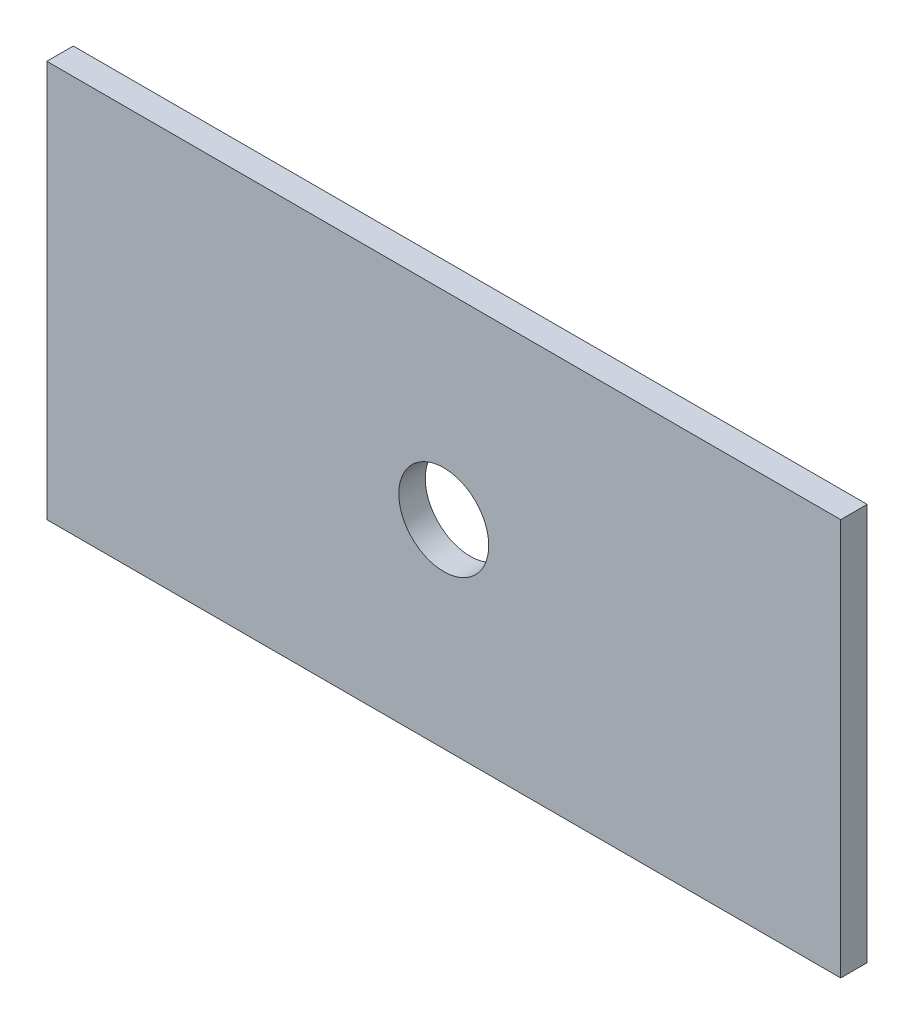
SolidWorks part; units mm, degrees
ref_plane "Front Plane" through (0, 0, 0) normal (0, 0, 1) x (1, 0, 0)
ref_plane "Top Plane" through (0, 0, 0) normal (0, 1, 0) x (1, 0, 0)
ref_plane "Right Plane" through (0, 0, 0) normal (1, 0, 0) x (0, 0, -1)
sketch "Sketch1" plane through (0, 0, 0) normal (0, 0, 1) x (1, 0, 0)
  line L1 (0, 0) -> (30, 0)
  line L2 (0, 0) -> (0, 15)
  line L3 (0, 15) -> (30, 15)
  line L4 (30, 0) -> (30, 15)
  dimension "D1" = 15
  dimension "D2" = 30
extrude "Boss-Extrude1" add sketch "Sketch1" along normal blind 1
hole_wizard "M3 Clearance Hole1" positions "Sketch2" profile "Sketch3" hole size "M3" standard "ANSI Metric" end condition through all
sketch "Sketch2" plane through (0, 0, 0) normal (0, 0, -1) x (-1, 0, 0)
  line L0 (-30, 15) -> (0, 15) construction
  line L1 (-30, 0) -> (-30, 15) construction
  point P0 (-15, 7.5)
  point P5 (-15, 15)
  point P8 (-30, 7.5)
sketch "Sketch3" plane through (15, 7.5, 0) normal (1, 0, 0) x (0, 1, 0)
  line L0 (0, 0) -> (0, 1)
  line L1 (0, 1) -> (1.7, 1)
  line L2 (1.7, 1) -> (1.7, 0)
  line L5 (1.7, 0) -> (0, 0)
  line L11 (0, -6.35) -> (0, 107.95) construction
  dimension "Thru Hole Dia." = 3.4
  dimension "Thru Hole Depth" = 1
